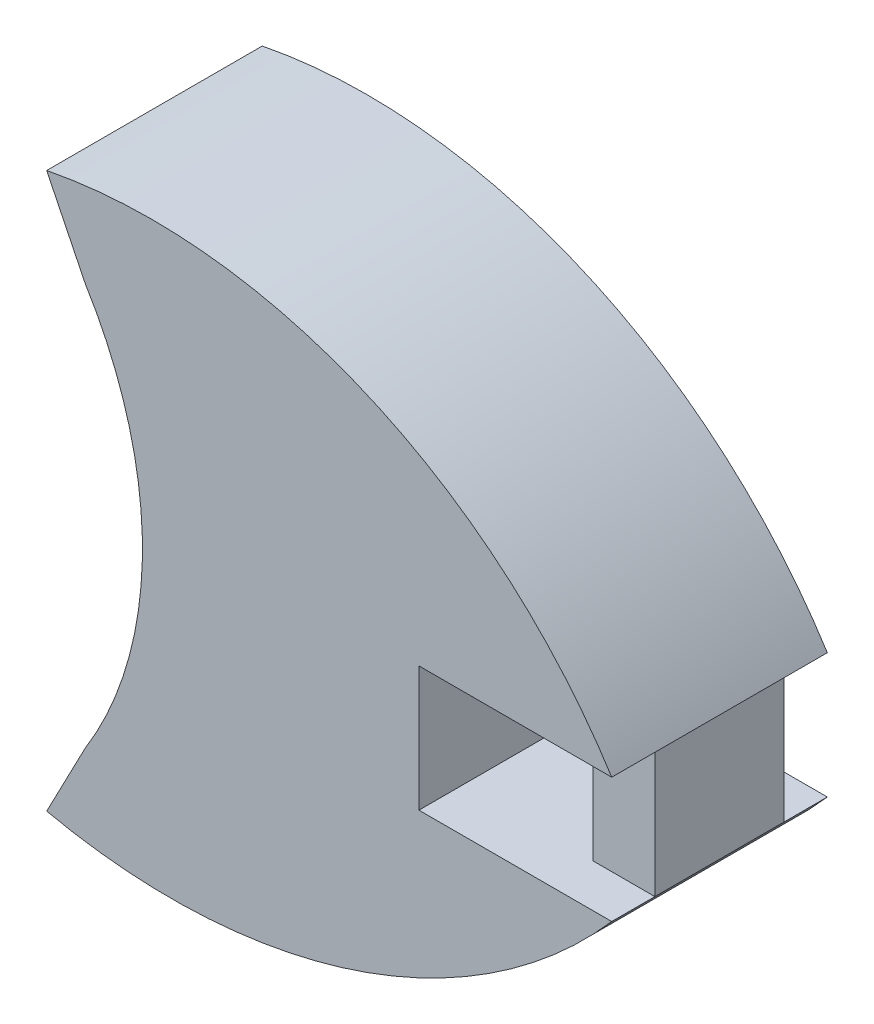
SolidWorks part; units mm, degrees
ref_plane "前基準面" through (0, 0, 0) normal (0, 0, 1) x (1, 0, 0)
ref_plane "上基準面" through (0, 0, 0) normal (0, 1, 0) x (1, 0, 0)
ref_plane "右基準面" through (0, 0, 0) normal (1, 0, 0) x (0, 0, -1)
sketch "草圖1" plane through (0, 0, 0) normal (0, 0, 1) x (1, 0, 0)
  line L0 (0, 0) -> (-8.9425, 0)
  line L1 (-8.9425, 0) -> (-8.9425, -5.7961)
  line L2 (-8.9425, -5.7961) -> (0, -5.7961)
  line L3 (-26.2093, 11.2664) -> (-24.419, 7.6112)
  line L4 (-26.2093, -14.4695) -> (-24.419, -11.038)
  arc A0 (0, -5.7961) -> (-26.2093, -14.4695) centre (-20.441, 12.0361) cw
  arc A1 (0, 0) -> (-26.2093, 11.2664) centre (-21.3274, -13.4957) ccw
  arc A2 (-24.419, 7.6112) -> (-24.419, -11.038) centre (-39.4875, -1.7134) cw
  point P14 (0, 0)
extrude "填料-伸長1" add sketch "草圖1" along normal blind 10 contours A1 L3 A2 L4 A0 L2 L1 L0
sketch "草圖2" plane through (0, 0, 0) normal (0, 0, 1) x (1, 0, 0)
  line L0 (-8.9425, -5.7961) -> (0, -5.7961) construction
  line L1 (0, 0) -> (-2.8596, 0)
  line L2 (0, 0) -> (0, -5.7961)
  line L3 (0, -5.7961) -> (-2.8596, -5.7961)
  line L4 (-2.8596, 0) -> (-2.8596, -5.7961)
extrude "填料-伸長2" add sketch "草圖2" along normal blind 10
sketch "草圖11" plane through (0, 0, 10) normal (0, 0, 1) x (1, 0, 0)
  line L1 (-2.8596, 0) -> (0, 0)
  line L2 (-2.8596, 0) -> (-2.8596, -5.7961)
  line L3 (-2.8596, -5.7961) -> (0, -5.7961)
  line L4 (0, 0) -> (0, -5.7961)
extrude "除料-伸長8" cut sketch "草圖11" against normal blind 2
sketch "草圖12" plane through (0, 0, 0) normal (0, 0, -1) x (-1, 0, 0)
  line L1 (0, 0) -> (2.8596, 0)
  line L2 (0, 0) -> (0, -5.7961)
  line L3 (0, -5.7961) -> (2.8596, -5.7961)
  line L4 (2.8596, 0) -> (2.8596, -5.7961)
extrude "除料-伸長9" cut sketch "草圖12" against normal blind 2
